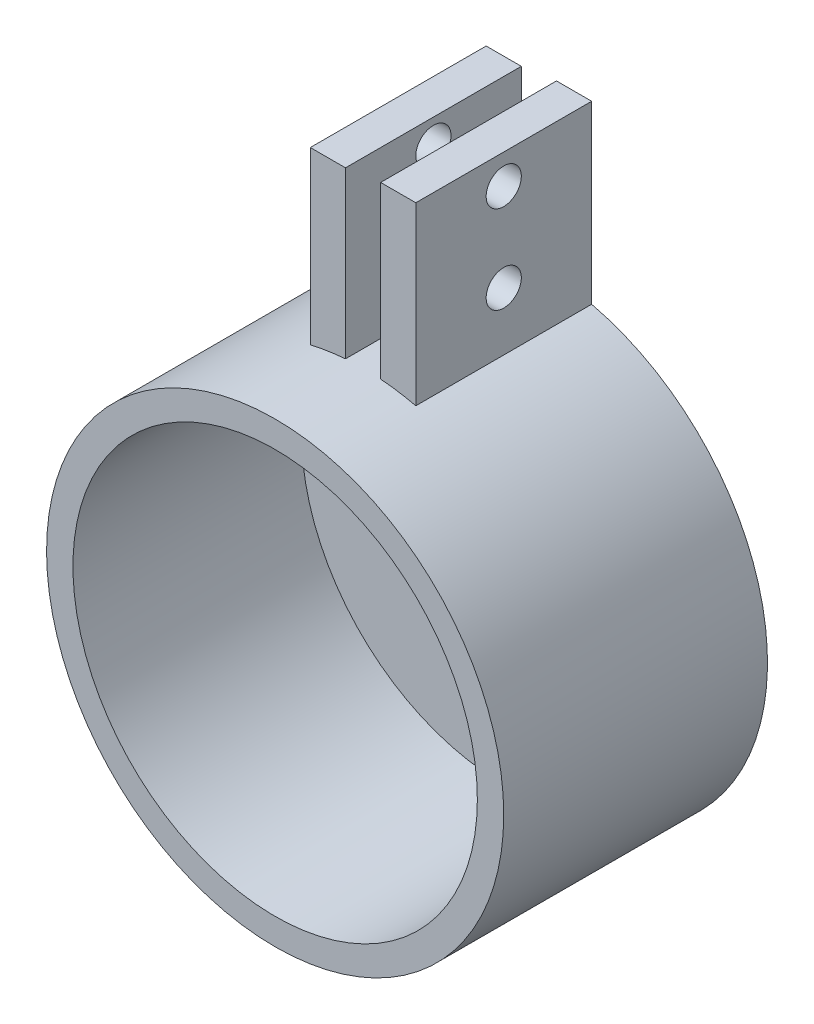
SolidWorks part; units mm, degrees
ref_plane "Front Plane" through (0, 0, 0) normal (0, 0, 1) x (1, 0, 0)
ref_plane "Top Plane" through (0, 0, 0) normal (0, 1, 0) x (1, 0, 0)
ref_plane "Right Plane" through (0, 0, 0) normal (1, 0, 0) x (0, 0, -1)
sketch "Sketch5" plane through (0, 0, 0) normal (0, 0, 1) x (1, 0, 0)
  circle A0 centre (0, 0) radius 11.5
  circle A1 centre (0, 0) radius 13
extrude "Boss-Extrude1" add sketch "Sketch5" along normal blind 15
sketch "Sketch6" plane through (0, 0, 0) normal (0, 0, 1) x (1, 0, 0)
  circle A0 centre (0, 0) radius 13
extrude "Boss-Extrude2" add sketch "Sketch6" along normal blind 2
sketch "Sketch7" plane through (0, 0, 0) normal (0, 0, -1) x (-1, 0, 0)
  line L0 (-3, 12.6491) -> (-3, 22.6491)
  circle A0 centre (0, 0) radius 13 construction
  dimension "D1" = 10
  dimension "D2" = 3
sketch "Sketch8" plane through (0, 0, 0) normal (0, 0, -1) x (-1, 0, 0)
  line L0 (3, 12.6491) -> (3, 22.3693)
  circle A0 centre (0, 0) radius 13 construction
  dimension "D1" = 3
extrude "Extrude-Thin1" add sketch "Sketch7" against normal blind 10 thin
extrude "Extrude-Thin2" add sketch "Sketch8" against normal blind 10 thin thin type one direction reverse wall 2
sketch "Sketch9" plane through (-3, 0, 0) normal (-1, 0, 0) x (0, 0, 1)
  line L0 (0, 12.6491) -> (0, 22.3693) construction
  circle A0 centre (5, 15.9615) radius 1
  circle A1 centre (5, 20.9615) radius 1
  dimension "D1" = 5
  dimension "D2" = 5
  dimension "D3" = 3
  dimension "D4" = 5
extrude "Cut-Extrude1" cut sketch "Sketch9" against normal through all both and the other way through all
